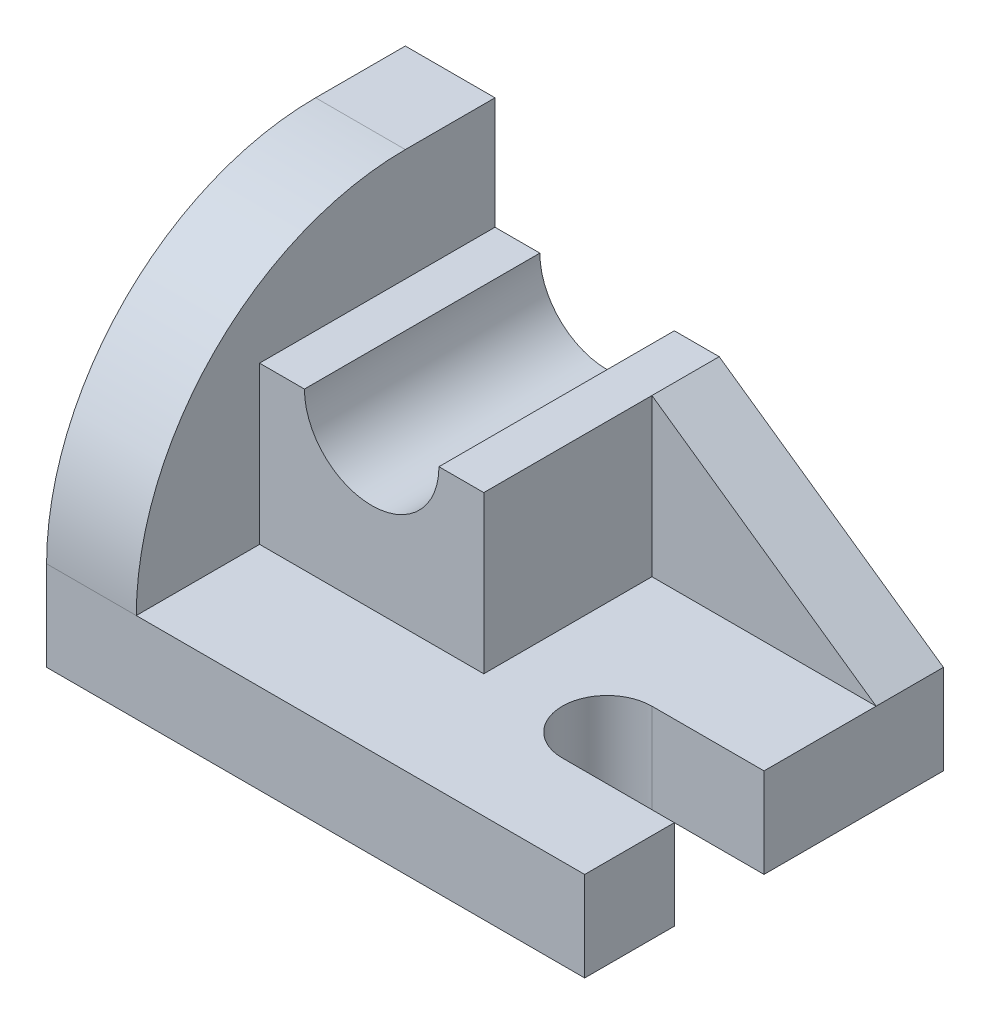
SolidWorks part; units mm, degrees
ref_plane "Front Plane" through (0, 0, 0) normal (0, 0, 1) x (1, 0, 0)
ref_plane "Top Plane" through (0, 0, 0) normal (0, 1, 0) x (1, 0, 0)
ref_plane "Right Plane" through (0, 0, 0) normal (1, 0, 0) x (0, 0, -1)
sketch "Sketch1" plane through (0, 0, 0) normal (0, 1, 0) x (1, 0, 0)
  line L1 (0, 0) -> (96, 0)
  line L2 (0, 0) -> (0, 64)
  line L3 (0, 64) -> (96, 64)
  line L4 (96, 0) -> (96, 64)
  dimension "D1" = 96
  dimension "D2" = 64
extrude "Boss-Extrude1" add sketch "Sketch1" along normal blind 16
sketch "Sketch2" plane through (0, 16, 0) normal (0, 1, 0) x (1, 0, 0)
  line L0 (96, 24) -> (76, 24) construction
  line L1 (96, 0) -> (96, 64) construction
  line L2 (96, 16) -> (76, 16)
  line L3 (96, 32) -> (76, 32)
  line L4 (0, 0) -> (96, 0) construction
  arc A0 (96, 16) -> (96, 32) centre (96, 24) ccw
  arc A1 (76, 32) -> (76, 16) centre (76, 24) ccw
  point P4 (86, 24)
  dimension "D1" = 8
  dimension "D2" = 20
  dimension "D3" = 16
extrude "Cut-Extrude1" cut sketch "Sketch2" against normal blind 16
sketch "Sketch3" plane through (0, 0, 0) normal (-1, 0, 0) x (0, 0, 1)
  line L1 (-64, 0) -> (0, 0)
  line L2 (-64, 0) -> (-64, 64)
  line L3 (-64, 64) -> (-48, 64)
  line L4 (0, 0) -> (0, 16)
  arc A0 (0, 16) -> (-48, 64) centre (-48, 16) ccw
  point P7 (0, 64)
  dimension "D3" = 48
  dimension "D1" = 64
  dimension "D2" = 64
extrude "Boss-Extrude2" add sketch "Sketch3" against normal blind 16
sketch "Sketch4" plane through (0, 16, 0) normal (0, 1, 0) x (1, 0, 0)
  line L0 (16, 0) -> (96, 0) construction
  line L1 (16, 64) -> (56, 64)
  line L2 (16, 64) -> (16, 22)
  line L3 (16, 22) -> (56, 22)
  line L4 (56, 64) -> (56, 22)
  dimension "D1" = 40
  dimension "D2" = 22
extrude "Boss-Extrude3" add sketch "Sketch4" along normal blind 28
sketch "Sketch5" plane through (0, 0, -22) normal (0, 0, 1) x (1, 0, 0)
  line L0 (16, 44) -> (56, 44) construction
  circle A0 centre (36, 44) radius 12
  dimension "D1" = 24
extrude "Cut-Extrude3" cut sketch "Sketch5" against normal blind 46 contours A0
sketch "Sketch8" plane through (0, 0, -64) normal (0, 0, -1) x (-1, 0, 0)
  line L0 (-56, 44) -> (-96, 16)
  line L1 (-96, 16) -> (-56, 16)
  line L2 (-56, 16) -> (-56, 44)
extrude "Boss-Extrude4" add sketch "Sketch8" against normal blind 12
